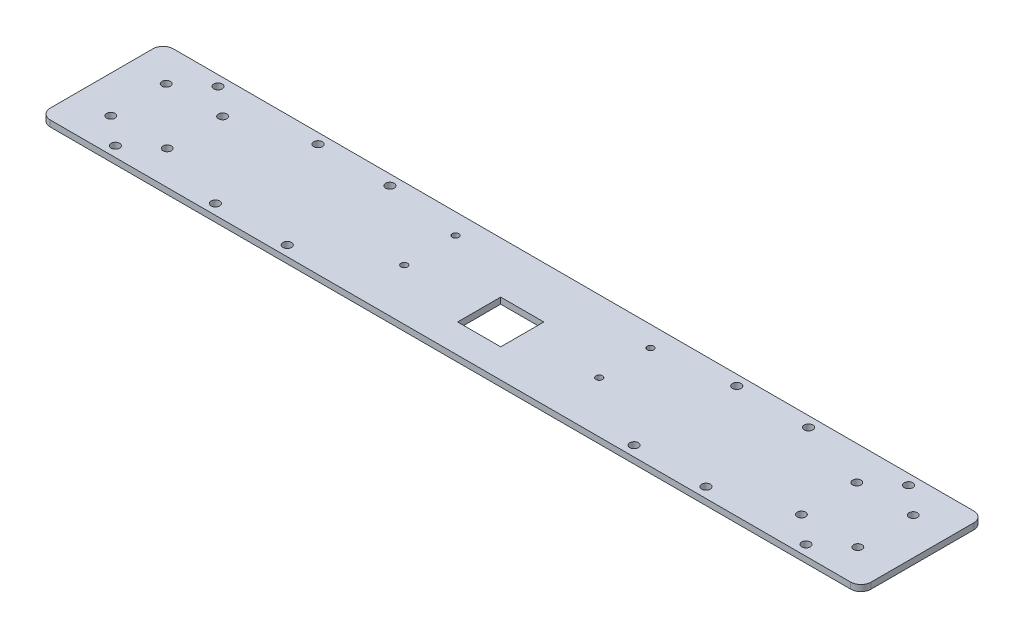
SolidWorks part; units mm, degrees
material "Thornel Mat VMA"
ref_plane "前视基准面" through (0, 0, 0) normal (0, 0, 1) x (1, 0, 0)
ref_plane "上视基准面" through (0, 0, 0) normal (0, 1, 0) x (1, 0, 0)
ref_plane "右视基准面" through (0, 0, 0) normal (1, 0, 0) x (0, 0, -1)
sketch "草图1" plane through (0, 0, 0) normal (0, 1, 0) x (1, 0, 0)
  line L0 (32.8259, -88.8718) -> (32.8259, 46.1282) construction
  line L1 (-167.1741, -13.8718) -> (232.8259, -13.8718)
  line L2 (-167.1741, -13.8718) -> (-167.1741, 46.1282)
  line L3 (-167.1741, 46.1282) -> (232.8259, 46.1282)
  line L4 (232.8259, -13.8718) -> (232.8259, 46.1282)
  line L5 (-14.6741, 36.1282) -> (80.3259, 36.1282) construction
  line L6 (-14.6741, 11.1282) -> (80.3259, 11.1282) construction
  line L7 (-87.1741, -88.8718) -> (152.8259, -88.8718)
  line L8 (-87.1741, -88.8718) -> (-87.1741, -13.8718)
  line L9 (-87.1741, -13.8718) -> (152.8259, -13.8718)
  line L10 (152.8259, -88.8718) -> (152.8259, -13.8718)
  line L11 (22.3259, 10.6282) -> (43.3259, 10.6282) construction
  line L12 (22.3259, 0.1282) -> (43.3259, 0.1282)
  line L13 (22.3259, 0.1282) -> (22.3259, 21.1282)
  line L14 (22.3259, 21.1282) -> (43.3259, 21.1282)
  line L15 (43.3259, 0.1282) -> (43.3259, 21.1282)
  line L16 (7.8259, -54.8718) -> (57.8259, -54.8718) construction
  line L17 (7.8259, -29.8718) -> (57.8259, -29.8718) construction
  line L18 (7.8259, -29.8718) -> (7.8259, -79.8718) construction
  line L19 (7.8259, -79.8718) -> (57.8259, -79.8718) construction
  line L20 (57.8259, -29.8718) -> (57.8259, -79.8718) construction
  line L21 (32.8259, 21.1282) -> (32.8259, 0.1282) construction
  line L22 (7.8259, -29.8718) -> (29.2904, -51.3362) construction
  line L23 (57.8259, -29.8718) -> (7.8259, -79.8718) construction
  line L31 (36.3615, -58.4073) -> (57.8259, -79.8718) construction
  circle A0 centre (-14.6741, 36.1282) radius 1.6
  circle A1 centre (-14.6741, 11.1282) radius 1.6
  circle A2 centre (80.3259, 11.1282) radius 1.6
  circle A3 centre (80.3259, 36.1282) radius 1.6
  circle A4 centre (7.8259, -29.8718) radius 1.6
  circle A5 centre (7.8259, -79.8718) radius 1.6
  circle A6 centre (57.8259, -79.8718) radius 1.6
  circle A7 centre (57.8259, -29.8718) radius 1.6
  circle A8 centre (32.8259, -54.8718) radius 20
  point P0 (0, 0)
  point P6 (0, -121.2547)
  point P16 (32.8259, 36.1282)
  point P19 (32.8259, 11.1282)
  point P23 (32.8259, 13.1501)
  point P30 (32.8259, -20.0664)
  point P35 (32.8259, -29.8718)
  point P44 (4.2904, -33.4073)
  point P45 (54.2904, -83.4073)
  point P46 (11.3615, -26.3362)
  point P47 (61.3615, -76.3362)
  point P48 (54.2904, -26.3362)
  point P49 (4.2904, -76.3362)
  point P50 (61.3615, -33.4073)
  point P51 (11.3615, -83.4073)
  dimension "D8" = 21
  dimension "D13" = 3.2
  dimension "D9" = 40
  dimension "D1" = 400
  dimension "D2" = 60
  dimension "D3" = 75
  dimension "D4" = 240
  dimension "D5" = 10
  dimension "D6" = 95
  dimension "D7" = 25
  dimension "D10" = 30
  dimension "D11" = 15
  dimension "D12" = 50
  dimension "D14" = 10.5
extrude "构型与裁判孔" add sketch "草图1" along normal blind 3 contours L1 L4 L3 L2 A3 L15 L12 L13 L14 A0 A1 A2 A4 A7 | L7 L10 L1 L8 A6 A5
sketch "草图2" plane through (0, 3, 0) normal (0, 1, 0) x (1, 0, 0)
  line L0 (-167.1741, 16.1282) -> (232.8259, 16.1282) construction
  line L1 (-167.1741, -13.8718) -> (-167.1741, 46.1282) construction
  line L2 (232.8259, -13.8718) -> (232.8259, 46.1282) construction
  line L3 (32.8259, 46.1282) -> (32.8259, -88.8718) construction
  line L4 (-167.1741, 46.1282) -> (232.8259, 46.1282) construction
  line L5 (-87.1741, -88.8718) -> (152.8259, -88.8718) construction
  line L6 (-149.1741, 2.6282) -> (-149.1741, 29.6282) construction
  line L7 (-121.6741, 2.6282) -> (-121.6741, 29.6282) construction
  line L8 (-149.1741, 29.6282) -> (-121.6741, 29.6282) construction
  line L9 (-51.6741, -8.8718) -> (-51.6741, 41.1282) construction
  line L10 (-135.4241, 29.6282) -> (-135.4241, 46.1282) construction
  line L11 (-135.4241, 41.1282) -> (-86.6741, 41.1282) construction
  circle A0 centre (-149.1741, 29.6282) radius 2.05
  circle A1 centre (-149.1741, 2.6282) radius 2.05
  circle A2 centre (-121.6741, 29.6282) radius 2.05
  circle A3 centre (-121.6741, 2.6282) radius 2.05
  circle A4 centre (-51.6741, 41.1282) radius 2.1
  circle A5 centre (-86.6741, 41.1282) radius 2.1
  circle A6 centre (-51.6741, -8.8718) radius 2.1
  circle A7 centre (-86.6741, -8.8718) radius 2.1
  circle A8 centre (-135.4241, 41.1282) radius 2.1
  circle A9 centre (-135.4241, -8.8718) radius 2.1
  circle A10 centre (201.0759, -8.8718) radius 2.1
  circle A11 centre (201.0759, 41.1282) radius 2.1
  circle A12 centre (152.3259, -8.8718) radius 2.1
  circle A13 centre (117.3259, -8.8718) radius 2.1
  circle A14 centre (152.3259, 41.1282) radius 2.1
  circle A15 centre (117.3259, 41.1282) radius 2.1
  circle A16 centre (187.3259, 2.6282) radius 2.05
  circle A17 centre (187.3259, 29.6282) radius 2.05
  circle A18 centre (214.8259, 2.6282) radius 2.05
  circle A19 centre (214.8259, 29.6282) radius 2.05
  point P15 (-149.1741, 16.1282)
  point P20 (-121.6741, 16.1282)
  point P25 (-51.6741, 16.1282)
  dimension "D2" = 4.1
  dimension "D4" = 5
  dimension "D5" = 4.2
  dimension "D7" = 2
  dimension "D8" = 18
  dimension "D3" = 45.5
  dimension "D1" = 27
  dimension "D6" = 70
extrude "切除-拉伸1" cut sketch "草图2" against normal through all
fillet "圆角1" radius 5 8 edges at (-87.1741, 1.5, 13.8718) (152.8259, 1.5, 13.8718) (-167.1741, 1.5, 13.8718) (-167.1741, 1.5, -46.1282) (232.8259, 1.5, -46.1282) (232.8259, 1.5, 13.8718) (152.8259, 1.5, 88.8718) (-87.1741, 1.5, 88.8718)
sketch "Sketch1" plane through (0, 0, 0) normal (0, 1, 0) x (1, 0, 0)
  line L0 (-162.1741, -13.8718) -> (-92.1741, -13.8718) construction
  line L1 (-87.1741, -83.8718) -> (-87.1741, -18.8718) construction
  line L2 (32.8259, 46.1282) -> (32.8259, -164.9495) construction
  line L3 (-162.1741, 46.1282) -> (227.8259, 46.1282) construction
  line L4 (-72.1741, -33.8718) -> (-72.1741, -68.8718) construction
  line L5 (-32.1741, -33.8718) -> (-32.1741, -68.8718) construction
  line L6 (-32.1741, -68.8718) -> (-32.1741, -33.8718) construction
  line L7 (-42.1741, -68.8718) -> (-42.1741, -33.8718)
  line L8 (-22.1741, -68.8718) -> (-22.1741, -33.8718)
  line L9 (97.8259, -68.8718) -> (97.8259, -33.8718) construction
  line L10 (107.8259, -68.8718) -> (107.8259, -33.8718)
  line L11 (87.8259, -68.8718) -> (87.8259, -33.8718)
  circle A0 centre (-72.1741, -33.8718) radius 2.1
  circle A1 centre (-72.1741, -68.8718) radius 2.1
  circle A2 centre (137.8259, -68.8718) radius 2.1
  circle A3 centre (137.8259, -33.8718) radius 2.1
  arc A4 (-42.1741, -68.8718) -> (-22.1741, -68.8718) centre (-32.1741, -68.8718) ccw
  arc A5 (-22.1741, -33.8718) -> (-42.1741, -33.8718) centre (-32.1741, -33.8718) ccw
  arc A6 (107.8259, -68.8718) -> (87.8259, -68.8718) centre (97.8259, -68.8718) cw
  arc A7 (87.8259, -33.8718) -> (107.8259, -33.8718) centre (97.8259, -33.8718) cw
  point P18 (-32.1741, -51.3718)
  point P20 (-32.1741, -51.3718)
  point P27 (97.8259, -51.3718)
  dimension "D1" = 4.2
  dimension "D2" = 20
  dimension "D3" = 35
  dimension "D4" = 15
  dimension "D5" = 15
  dimension "D7" = 10
  dimension "D6" = 40
extrude "Cut-Extrude4" cut sketch "Sketch1" along normal through all
sketch "草图3" plane through (0, 3, 0) normal (0, 1, 0) x (1, 0, 0)
  line L0 (-92.1741, -13.8718) -> (157.8259, -13.8718)
  line L9 (-167.1741, 41.1282) -> (-167.1741, -8.8718)
  line L10 (-162.1741, -13.8718) -> (-92.1741, -13.8718)
  line L11 (-87.1741, -18.8718) -> (-87.1741, -83.8718)
  line L12 (-82.1741, -88.8718) -> (147.8259, -88.8718)
  line L13 (152.8259, -83.8718) -> (152.8259, -18.8718)
  line L14 (157.8259, -13.8718) -> (227.8259, -13.8718)
  line L15 (232.8259, -8.8718) -> (232.8259, 41.1282)
  line L16 (227.8259, 46.1282) -> (-162.1741, 46.1282)
  line L17 (-167.1741, 41.1282) -> (-167.1741, -8.8718)
  line L18 (-162.1741, -13.8718) -> (-92.1741, -13.8718)
  line L19 (-87.1741, -18.8718) -> (-87.1741, -83.8718)
  line L20 (-82.1741, -88.8718) -> (147.8259, -88.8718)
  line L21 (152.8259, -83.8718) -> (152.8259, -18.8718)
  line L22 (157.8259, -13.8718) -> (227.8259, -13.8718)
  line L23 (232.8259, -8.8718) -> (232.8259, 41.1282)
  line L24 (227.8259, 46.1282) -> (-162.1741, 46.1282)
  arc A9 (-167.1741, -8.8718) -> (-162.1741, -13.8718) centre (-162.1741, -8.8718) ccw
  arc A10 (-87.1741, -18.8718) -> (-92.1741, -13.8718) centre (-92.1741, -18.8718) ccw
  arc A11 (-87.1741, -83.8718) -> (-82.1741, -88.8718) centre (-82.1741, -83.8718) ccw
  arc A12 (147.8259, -88.8718) -> (152.8259, -83.8718) centre (147.8259, -83.8718) ccw
  arc A13 (157.8259, -13.8718) -> (152.8259, -18.8718) centre (157.8259, -18.8718) ccw
  arc A14 (227.8259, -13.8718) -> (232.8259, -8.8718) centre (227.8259, -8.8718) ccw
  arc A15 (232.8259, 41.1282) -> (227.8259, 46.1282) centre (227.8259, 41.1282) ccw
  arc A16 (-162.1741, 46.1282) -> (-167.1741, 41.1282) centre (-162.1741, 41.1282) ccw
  arc A17 (-167.1741, -8.8718) -> (-162.1741, -13.8718) centre (-162.1741, -8.8718) ccw
  arc A18 (-87.1741, -18.8718) -> (-92.1741, -13.8718) centre (-92.1741, -18.8718) ccw
  arc A19 (-87.1741, -83.8718) -> (-82.1741, -88.8718) centre (-82.1741, -83.8718) ccw
  arc A20 (147.8259, -88.8718) -> (152.8259, -83.8718) centre (147.8259, -83.8718) ccw
  arc A21 (157.8259, -13.8718) -> (152.8259, -18.8718) centre (157.8259, -18.8718) ccw
  arc A22 (227.8259, -13.8718) -> (232.8259, -8.8718) centre (227.8259, -8.8718) ccw
  arc A23 (232.8259, 41.1282) -> (227.8259, 46.1282) centre (227.8259, 41.1282) ccw
  arc A24 (-162.1741, 46.1282) -> (-167.1741, 41.1282) centre (-162.1741, 41.1282) ccw
  dimension "D1" = 0
extrude "切除-拉伸2" cut sketch "草图3" against normal blind 10 contours A21 L0 A18 L19 A19 L20 A20 L21
